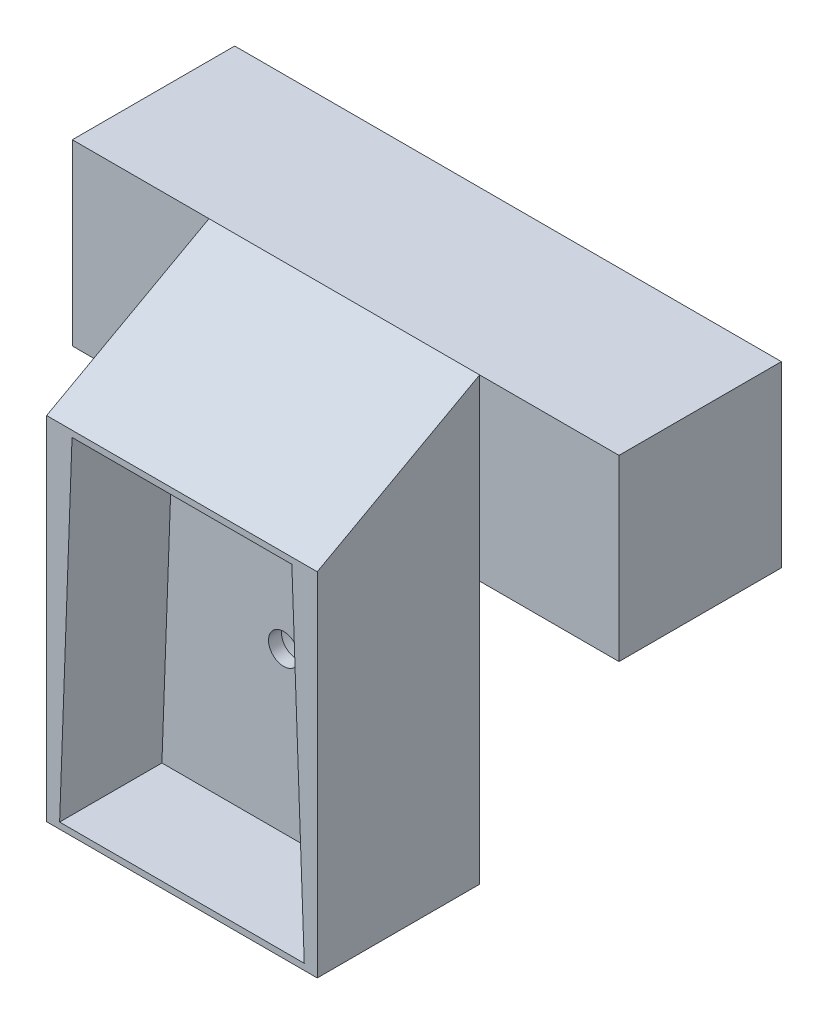
SolidWorks part; units mm, degrees
ref_plane "Přední rovina" through (0, 0, 0) normal (0, 0, 1) x (1, 0, 0)
ref_plane "Horní rovina" through (0, 0, 0) normal (0, 1, 0) x (1, 0, 0)
ref_plane "Pravá rovina" through (0, 0, 0) normal (1, 0, 0) x (0, 0, -1)
sketch "Skica1" plane through (0, 0, 0) normal (0, 0, 1) x (1, 0, 0)
  line L1 (0, 0) -> (101, 0)
  line L2 (0, 0) -> (0, 33)
  line L3 (0, 33) -> (101, 33)
  line L4 (101, 0) -> (101, 33)
  dimension "D1" = 33
  dimension "D2" = 101
extrude "Přidat vysunutím1" add sketch "Skica1" along normal blind 30
sketch "Skica2" plane through (0, 0, 30) normal (0, 0, 1) x (1, 0, 0)
  line L0 (101, 33) -> (0, 33) construction
  line L1 (25.25, 16.5) -> (75.25, 16.5)
  line L2 (25.25, 16.5) -> (25.25, -48.5)
  line L3 (25.25, -48.5) -> (75.25, -48.5)
  line L4 (75.25, 16.5) -> (75.25, -48.5)
  dimension "D1" = 50
  dimension "D2" = 65
  dimension "D3" = 25.25
  dimension "D4" = 16.5
extrude "Přidat vysunutím2" add sketch "Skica2" along normal blind 30 contours L1 L4 L3 L2
sketch "Skica3" plane through (25.25, 0, 0) normal (-1, 0, 0) x (0, 0, 1)
  line L0 (30, 33) -> (60, 16.5)
  line L1 (60, 16.5) -> (30, 16.5)
  line L2 (30, 33) -> (30, 0) construction
  line L3 (30, 16.5) -> (30, 33)
extrude "Přidat vysunutím3" add sketch "Skica3" against normal up to vertex (50 mm away) up to point (75.25, 16.5, 60)
sketch "Skica6" plane through (0, 0, 60) normal (0, 0, 1) x (1, 0, 0)
  line L0 (29.945, 15.35) -> (70.555, 15.35)
  line L3 (70.555, 15.35) -> (72.85, -47.35)
  line L4 (25.25, 16.5) -> (25.25, -48.5) construction
  line L5 (29.945, 15.35) -> (70.555, 15.35) construction
  line L7 (72.85, -47.35) -> (27.65, -47.35)
  line L11 (29.945, 15.35) -> (27.65, -47.35)
  line L12 (25.25, 16.5) -> (75.25, 16.5) construction
  dimension "D1" = 45.2
  dimension "D2" = 40.61
  dimension "D3" = 2.4
  dimension "D4" = 4.695
  dimension "D5" = 62.7
  dimension "D6" = 1.15
extrude "Odebrat vysunutím5" cut sketch "Skica6" against normal offset from surface (18.9 mm away) 18.9 contours L0 L3 L7 L11 up to face at (50.25, -16, 60)
sketch "Skica17" plane through (0, 0, 41.1) normal (0, 0, 1) x (1, 0, 0)
  line L2 (27.65, -47.35) -> (72.85, -47.35) construction
  line L3 (29.945, 15.35) -> (27.65, -47.35) construction
  circle A0 centre (50.1441, -17.85) radius 2.8
  point P0 (50.1441, -17.85)
  point P3 (50.25, -47.35)
  dimension "D3" = 5.6
  dimension "D1" = 29.5
  dimension "D2" = 21.4
extrude "Odebrat vysunutím6" cut sketch "Skica17" against normal offset from surface (14.2 mm away) 14.2 up to face at (50.25, -16, 41.1)
sketch "Skica18" plane through (0, 0, 30) normal (0, 0, -1) x (-1, 0, 0)
  circle A0 centre (-50.1441, -17.85) radius 7.5
  dimension "D1" = 15
extrude "Odebrat vysunutím7" cut sketch "Skica18" against normal offset from surface (8.7 mm away) 8.7 up to face at (52.9441, -17.85, 30)
